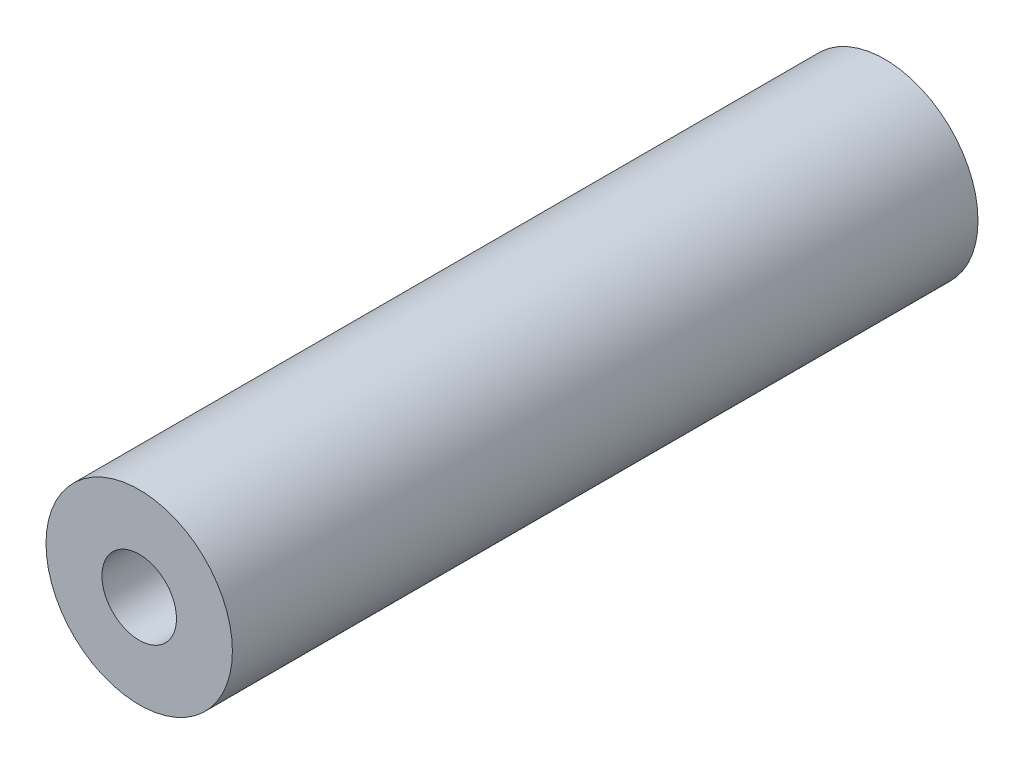
SolidWorks part; units mm, degrees
ref_plane "Front Plane" through (0, 0, 0) normal (0, 0, 1) x (1, 0, 0)
ref_plane "Top Plane" through (0, 0, 0) normal (0, 1, 0) x (1, 0, 0)
ref_plane "Right Plane" through (0, 0, 0) normal (1, 0, 0) x (0, 0, -1)
sketch "Standoff_OD8_ID3p2_profile" plane through (0, 0, 0) normal (0, 0, 1) x (1, 0, 0)
  circle A0 centre (0, 0) radius 4
  circle A1 centre (0, 0) radius 1.6
  dimension "D1" = 8
  dimension "D2" = 3.2
extrude "Standoff_OD8_ID3p2" add sketch "Standoff_OD8_ID3p2_profile" along normal blind 32
